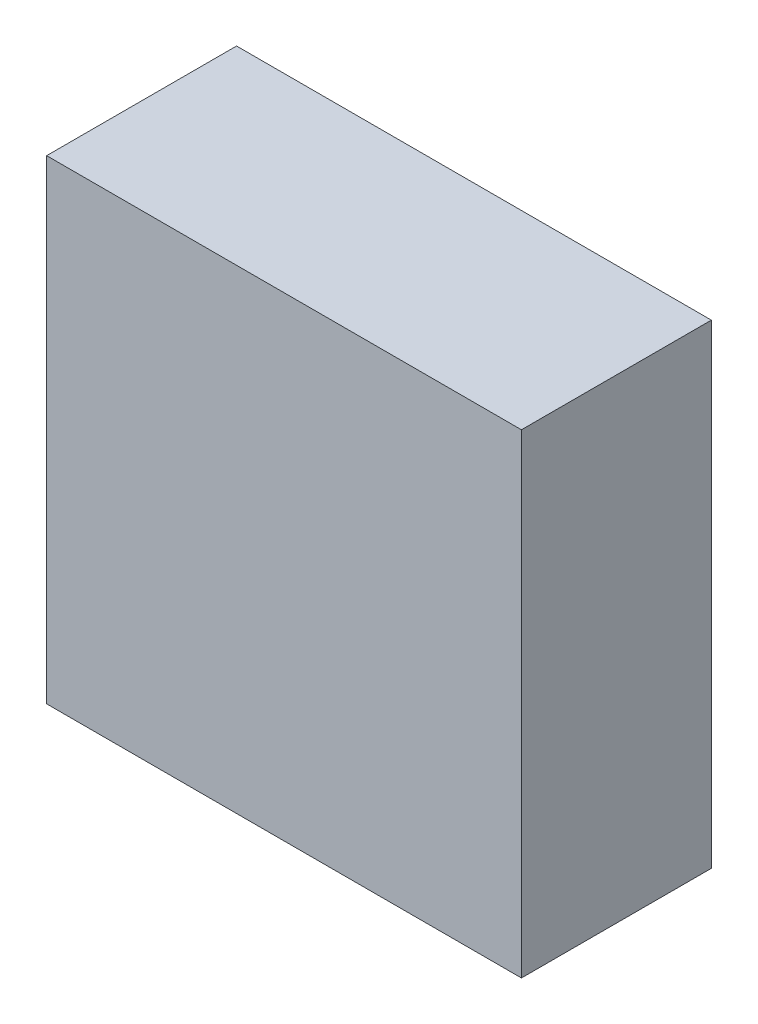
SolidWorks part; units mm, degrees
ref_plane "Спереди" through (0, 0, 0) normal (0, 0, 1) x (1, 0, 0)
ref_plane "Сверху" through (0, 0, 0) normal (0, 1, 0) x (1, 0, 0)
ref_plane "Справа" through (0, 0, 0) normal (1, 0, 0) x (0, 0, -1)
sketch "Skizze1" plane through (0, 0, 0) normal (0, 0, 1) x (1, 0, 0)
  line L1 (-1, 1) -> (1, 1)
  line L2 (-1, 1) -> (-1, -1)
  line L3 (-1, -1) -> (1, -1)
  line L4 (1, 1) -> (1, -1)
  dimension "D1" = 2
  dimension "D2" = 2
  dimension "D3" = 1
  dimension "D4" = 1
extrude "Aufsatz-Linear austragen1" add sketch "Skizze1" along normal blind 0.8
equation "\"2ьь\"=0.0397115"
